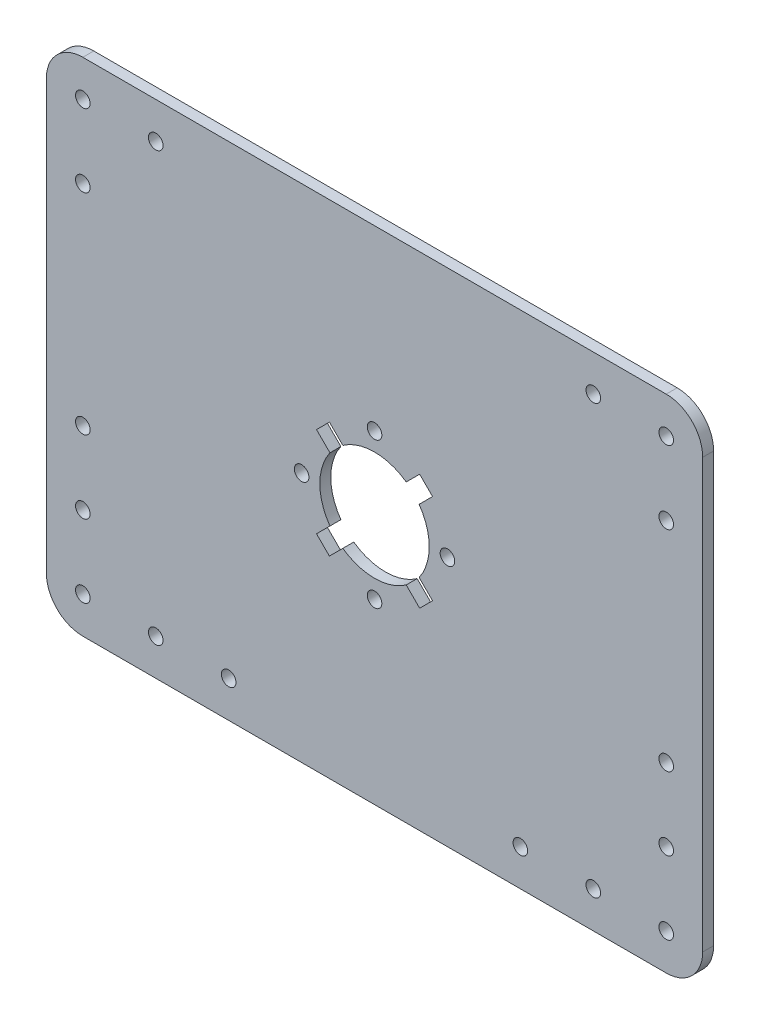
SolidWorks part; units mm, degrees
material "雪松树"
ref_plane "前视基准面" through (0, 0, 0) normal (0, 0, 1) x (1, 0, 0)
ref_plane "上视基准面" through (0, 0, 0) normal (0, 1, 0) x (1, 0, 0)
ref_plane "右视基准面" through (0, 0, 0) normal (1, 0, 0) x (0, 0, -1)
other "Configuration Table"
sketch "草图1" plane through (0, 0, 0) normal (0, 0, 1) x (1, 0, 0)
  line L0 (-12.3744, 15.9099) -> (-5.3033, 8.8388)
  line L1 (90, -68.75) -> (-90, -68.75)
  line L2 (90, -68.75) -> (90, 68.75)
  line L3 (90, 68.75) -> (-90, 68.75)
  line L4 (-90, -68.75) -> (-90, 68.75)
  line L5 (90, -68.75) -> (-90, 68.75) construction
  line L6 (90, 68.75) -> (-90, -68.75) construction
  line L7 (-12.3744, 15.9099) -> (-15.9099, 12.3744)
  line L8 (-5.3033, 8.8388) -> (-8.8388, 5.3033)
  line L9 (-15.9099, 12.3744) -> (-8.8388, 5.3033)
  line L10 (-12.3744, 15.9099) -> (-8.8388, 5.3033) construction
  line L11 (-5.3033, 8.8388) -> (-15.9099, 12.3744) construction
  line L12 (-1000, 0) -> (49000, 0) construction
  line L13 (-10.6066, 10.6066) -> (0, 0) construction
  line L14 (15.9099, 12.3744) -> (8.8388, 5.3033)
  line L15 (15.9099, 12.3744) -> (12.3744, 15.9099)
  line L16 (12.3744, 15.9099) -> (5.3033, 8.8388)
  line L17 (8.8388, 5.3033) -> (5.3033, 8.8388)
  line L18 (12.3744, -15.9099) -> (5.3033, -8.8388)
  line L19 (12.3744, -15.9099) -> (15.9099, -12.3744)
  line L20 (15.9099, -12.3744) -> (8.8388, -5.3033)
  line L21 (5.3033, -8.8388) -> (8.8388, -5.3033)
  line L22 (-15.9099, -12.3744) -> (-8.8388, -5.3033)
  line L23 (-15.9099, -12.3744) -> (-12.3744, -15.9099)
  line L24 (-12.3744, -15.9099) -> (-5.3033, -8.8388)
  line L25 (-8.8388, -5.3033) -> (-5.3033, -8.8388)
  circle A0 centre (0, 0) radius 15
  circle A1 centre (-20, 0) radius 2
  circle A2 centre (0, 20) radius 2
  circle A3 centre (20, 0) radius 2
  circle A4 centre (0, -20) radius 2
  point P0 (0, 0)
  point P12 (-10.6066, 10.6066)
  point P18 (0, 0)
  point P40 (0, 0)
  dimension "D3" = 30
  dimension "D4" = 4
  dimension "D5" = 20
  dimension "D1" = 137.5
  dimension "D2" = 180
  dimension "D6" = 4
  dimension "D7" = 10
  dimension "D8" = 5
  dimension "D9" = 45
  dimension "D10" = 20
  dimension "D11" = 4
extrude "凸台-拉伸1" add sketch "草图1" along normal mid plane 3 contours L4 L1 L2 L3 A4 A3 A2 A1 A0 L16 L15 L14 L20 L19 L18 L24 L23 L22 L9 L7 L0
fillet "圆角1" radius 10 4 edges at (90, -68.75, 0) (90, 68.75, 0) (-90, -68.75, 0) (-90, 68.75, 0)
sketch "草图3" plane through (0, 0, 1.5) normal (0, 0, 1) x (1, 0, 0)
  line L1 (80, -68.75) -> (-80, -68.75) construction
  line L2 (-90, -58.75) -> (-90, 58.75) construction
  line L3 (0, 102.434) -> (0, -111.9594) construction
  line L4 (-132.7682, 0) -> (138.0632, 0) construction
  circle A1 centre (-80, -58.75) radius 2
  circle A5 centre (-60, -58.75) radius 2
  circle A11 centre (-80, -38.75) radius 2
  circle A12 centre (-40, -58.75) radius 2
  circle A13 centre (-80, -18.75) radius 2
  circle A14 centre (80, -38.75) radius 2
  circle A15 centre (60, -58.75) radius 2
  circle A16 centre (80, -58.75) radius 2
  circle A17 centre (80, 58.75) radius 2
  circle A18 centre (60, 58.75) radius 2
  circle A19 centre (80, 38.75) radius 2
  circle A20 centre (-80, 38.75) radius 2
  circle A21 centre (-60, 58.75) radius 2
  circle A22 centre (-80, 58.75) radius 2
  circle A23 centre (40, -58.75) radius 2
  circle A24 centre (80, -18.75) radius 2
  dimension "D2" = 4
  dimension "D3" = 4
  dimension "D4" = 20
  dimension "D7" = 10
  dimension "D8" = 20
  dimension "D10" = 4
  dimension "D15" = 10
  dimension "D16" = 10
  dimension "D17" = 20
  dimension "D18" = 20
  dimension "D19" = 4
  dimension "D5" = 10
  dimension "D6" = 4
  dimension "D11" = 20
extrude "切除-拉伸4" cut sketch "草图3" against normal through all
